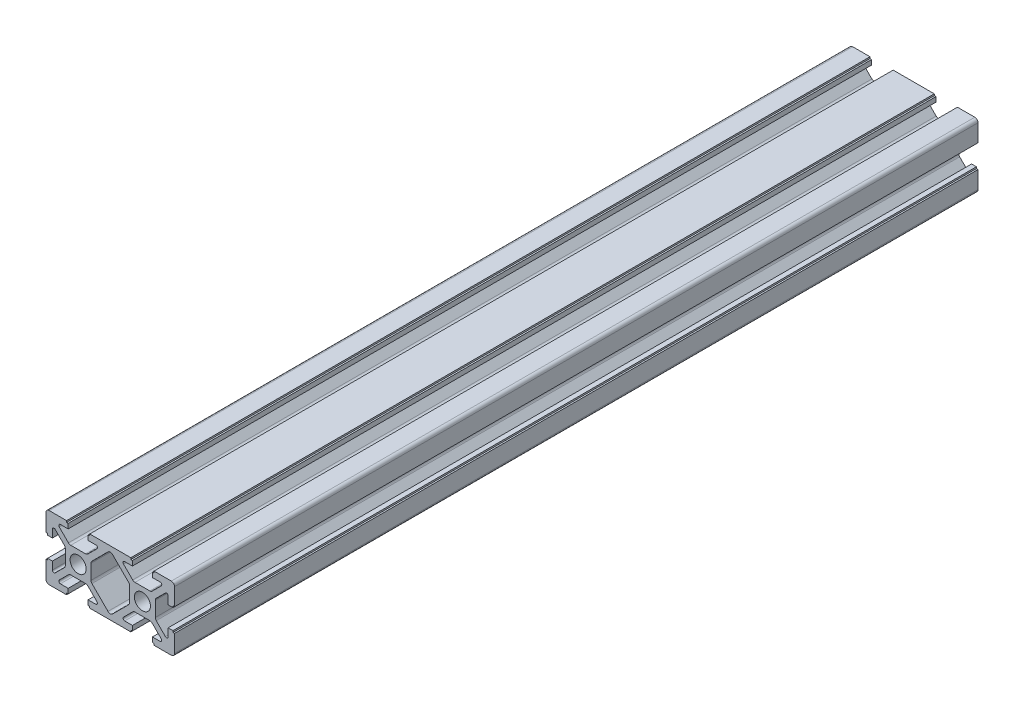
SolidWorks part; units mm, degrees
ref_plane "前视基准面" through (0, 0, 0) normal (0, 0, 1) x (1, 0, 0)
ref_plane "上视基准面" through (0, 0, 0) normal (0, 1, 0) x (1, 0, 0)
ref_plane "右视基准面" through (0, 0, 0) normal (1, 0, 0) x (0, 0, -1)
sketch "草图1" plane through (0, 0, 0) normal (0, 0, 1) x (1, 0, 0)
  line L0 (16.4868, 27.6666) -> (21.4868, 22.6666)
  line L1 (22.901, 22.6666) -> (27.901, 27.6666)
  line L2 (28.1939, 28.3737) -> (28.1939, 32.9997)
  line L3 (27.901, 33.7068) -> (22.901, 38.7068)
  line L4 (21.4868, 38.7068) -> (16.4868, 33.7068)
  line L5 (16.1939, 32.9997) -> (16.1939, 28.3737)
  line L6 (36.4868, 27.6666) -> (39.3403, 24.8131)
  line L7 (40.1939, 25.1666) -> (40.1939, 27.5867)
  line L8 (40.1939, 27.5867) -> (41.6939, 27.5867)
  line L9 (41.6939, 27.5867) -> (41.6939, 27.0867)
  line L10 (41.6939, 27.0867) -> (42.1939, 27.0867)
  line L11 (42.1939, 27.0867) -> (42.1939, 21.6867)
  line L12 (41.1939, 20.6867) -> (35.7939, 20.6867)
  line L13 (35.7939, 20.6867) -> (35.7939, 21.1867)
  line L14 (35.7939, 21.1867) -> (35.2939, 21.1867)
  line L15 (35.2939, 21.1867) -> (35.2939, 22.6867)
  line L16 (35.2939, 22.6867) -> (37.714, 22.6867)
  line L17 (38.0675, 23.5403) -> (35.214, 26.3938)
  line L18 (34.5069, 26.6867) -> (29.8809, 26.6867)
  line L19 (29.1738, 26.3938) -> (26.3202, 23.5403)
  line L20 (26.6738, 22.6867) -> (29.0939, 22.6867)
  line L21 (29.0939, 22.6867) -> (29.0939, 21.1867)
  line L22 (29.0939, 21.1867) -> (28.5939, 21.1867)
  line L23 (28.5939, 21.1867) -> (28.5939, 20.6867)
  line L24 (28.5939, 20.6867) -> (15.7939, 20.6867)
  line L25 (15.7939, 20.6867) -> (15.7939, 21.1867)
  line L26 (15.7939, 21.1867) -> (15.2939, 21.1867)
  line L27 (15.2939, 21.1867) -> (15.2939, 22.6867)
  line L28 (15.2939, 22.6867) -> (17.714, 22.6867)
  line L29 (18.0675, 23.5403) -> (15.214, 26.3938)
  line L30 (14.5069, 26.6867) -> (9.8809, 26.6867)
  line L31 (9.1738, 26.3938) -> (6.3202, 23.5403)
  line L32 (6.6738, 22.6867) -> (9.0939, 22.6867)
  line L33 (9.0939, 22.6867) -> (9.0939, 21.1867)
  line L34 (9.0939, 21.1867) -> (8.5939, 21.1867)
  line L35 (8.5939, 21.1867) -> (8.5939, 20.6867)
  line L36 (8.5939, 20.6867) -> (3.1939, 20.6867)
  line L37 (2.1939, 21.6867) -> (2.1939, 27.0867)
  line L38 (2.1939, 27.0867) -> (2.6939, 27.0867)
  line L39 (2.6939, 27.0867) -> (2.6939, 27.5867)
  line L40 (2.6939, 27.5867) -> (4.1939, 27.5867)
  line L41 (4.1939, 27.5867) -> (4.1939, 25.1666)
  line L42 (5.0474, 24.8131) -> (7.901, 27.6666)
  line L43 (8.1939, 28.3737) -> (8.1939, 32.9997)
  line L44 (7.901, 33.7068) -> (5.0474, 36.5604)
  line L45 (4.1939, 36.2068) -> (4.1939, 33.7867)
  line L46 (4.1939, 33.7867) -> (2.6939, 33.7867)
  line L47 (2.6939, 33.7867) -> (2.6939, 34.2867)
  line L48 (2.6939, 34.2867) -> (2.1939, 34.2867)
  line L49 (2.1939, 34.2867) -> (2.1939, 39.6867)
  line L50 (3.1939, 40.6867) -> (8.5939, 40.6867)
  line L51 (8.5939, 40.6867) -> (8.5939, 40.1867)
  line L52 (8.5939, 40.1867) -> (9.0939, 40.1867)
  line L53 (9.0939, 40.1867) -> (9.0939, 38.6867)
  line L54 (9.0939, 38.6867) -> (6.6738, 38.6867)
  line L55 (6.3202, 37.8332) -> (9.1738, 34.9796)
  line L56 (9.8809, 34.6867) -> (14.5069, 34.6867)
  line L57 (15.214, 34.9796) -> (18.0675, 37.8332)
  line L58 (17.714, 38.6867) -> (15.2939, 38.6867)
  line L59 (15.2939, 38.6867) -> (15.2939, 40.1867)
  line L60 (15.2939, 40.1867) -> (15.7939, 40.1867)
  line L61 (15.7939, 40.1867) -> (15.7939, 40.6867)
  line L62 (15.7939, 40.6867) -> (28.5939, 40.6867)
  line L63 (28.5939, 40.6867) -> (28.5939, 40.1867)
  line L64 (28.5939, 40.1867) -> (29.0939, 40.1867)
  line L65 (29.0939, 40.1867) -> (29.0939, 38.6867)
  line L66 (29.0939, 38.6867) -> (26.6738, 38.6867)
  line L67 (26.3202, 37.8332) -> (29.1738, 34.9796)
  line L68 (29.8809, 34.6867) -> (34.5069, 34.6867)
  line L69 (35.214, 34.9796) -> (38.0675, 37.8332)
  line L70 (37.714, 38.6867) -> (35.2939, 38.6867)
  line L71 (35.2939, 38.6867) -> (35.2939, 40.1867)
  line L72 (35.2939, 40.1867) -> (35.7939, 40.1867)
  line L73 (35.7939, 40.1867) -> (35.7939, 40.6867)
  line L74 (35.7939, 40.6867) -> (41.1939, 40.6867)
  line L75 (42.1939, 39.6867) -> (42.1939, 34.2867)
  line L76 (42.1939, 34.2867) -> (41.6939, 34.2867)
  line L77 (41.6939, 34.2867) -> (41.6939, 33.7867)
  line L78 (41.6939, 33.7867) -> (40.1939, 33.7867)
  line L79 (40.1939, 33.7867) -> (40.1939, 36.2068)
  line L80 (39.3403, 36.5604) -> (36.4868, 33.7068)
  line L81 (36.1939, 32.9997) -> (36.1939, 28.3737)
  arc A0 (17.714, 22.6867) -> (18.0675, 23.5403) centre (17.714, 23.1867) ccw
  arc A1 (15.214, 26.3938) -> (14.5069, 26.6867) centre (14.5069, 25.6867) ccw
  arc A2 (9.8809, 26.6867) -> (9.1738, 26.3938) centre (9.8809, 25.6867) ccw
  arc A3 (6.3202, 23.5403) -> (6.6738, 22.6867) centre (6.6738, 23.1867) ccw
  arc A4 (2.1939, 21.6867) -> (3.1939, 20.6867) centre (3.1939, 21.6867) ccw
  arc A5 (4.1939, 25.1666) -> (5.0474, 24.8131) centre (4.6939, 25.1666) ccw
  arc A6 (7.901, 27.6666) -> (8.1939, 28.3737) centre (7.1939, 28.3737) ccw
  arc A7 (8.1939, 32.9997) -> (7.901, 33.7068) centre (7.1939, 32.9997) ccw
  arc A8 (5.0474, 36.5604) -> (4.1939, 36.2068) centre (4.6939, 36.2068) ccw
  arc A9 (3.1939, 40.6867) -> (2.1939, 39.6867) centre (3.1939, 39.6867) ccw
  arc A10 (6.6738, 38.6867) -> (6.3202, 37.8332) centre (6.6738, 38.1867) ccw
  arc A11 (9.1738, 34.9796) -> (9.8809, 34.6867) centre (9.8809, 35.6867) ccw
  arc A12 (14.5069, 34.6867) -> (15.214, 34.9796) centre (14.5069, 35.6867) ccw
  arc A13 (18.0675, 37.8332) -> (17.714, 38.6867) centre (17.714, 38.1867) ccw
  arc A14 (26.6738, 38.6867) -> (26.3202, 37.8332) centre (26.6738, 38.1867) ccw
  arc A15 (29.1738, 34.9796) -> (29.8809, 34.6867) centre (29.8809, 35.6867) ccw
  arc A16 (34.5069, 34.6867) -> (35.214, 34.9796) centre (34.5069, 35.6867) ccw
  arc A17 (38.0675, 37.8332) -> (37.714, 38.6867) centre (37.714, 38.1867) ccw
  arc A18 (42.1939, 39.6867) -> (41.1939, 40.6867) centre (41.1939, 39.6867) ccw
  arc A19 (40.1939, 36.2068) -> (39.3403, 36.5604) centre (39.6939, 36.2068) ccw
  arc A20 (36.4868, 33.7068) -> (36.1939, 32.9997) centre (37.1939, 32.9997) ccw
  circle A21 centre (12.1939, 30.6867) radius 2.5
  circle A22 centre (32.1939, 30.6867) radius 2.5
  arc A23 (16.1939, 28.3737) -> (16.4868, 27.6666) centre (17.1939, 28.3737) ccw
  arc A24 (21.4868, 22.6666) -> (22.901, 22.6666) centre (22.1939, 23.3737) ccw
  arc A25 (27.901, 27.6666) -> (28.1939, 28.3737) centre (27.1939, 28.3737) ccw
  arc A26 (28.1939, 32.9997) -> (27.901, 33.7068) centre (27.1939, 32.9997) ccw
  arc A27 (22.901, 38.7068) -> (21.4868, 38.7068) centre (22.1939, 37.9997) ccw
  arc A28 (16.4868, 33.7068) -> (16.1939, 32.9997) centre (17.1939, 32.9997) ccw
  arc A29 (36.1939, 28.3737) -> (36.4868, 27.6666) centre (37.1939, 28.3737) ccw
  arc A30 (39.3403, 24.8131) -> (40.1939, 25.1666) centre (39.6939, 25.1666) ccw
  arc A31 (41.1939, 20.6867) -> (42.1939, 21.6867) centre (41.1939, 21.6867) ccw
  arc A32 (37.714, 22.6867) -> (38.0675, 23.5403) centre (37.714, 23.1867) ccw
  arc A33 (35.214, 26.3938) -> (34.5069, 26.6867) centre (34.5069, 25.6867) ccw
  arc A34 (29.8809, 26.6867) -> (29.1738, 26.3938) centre (29.8809, 25.6867) ccw
  arc A35 (26.3202, 23.5403) -> (26.6738, 22.6867) centre (26.6738, 23.1867) ccw
extrude "拉伸1" add sketch "草图1" along normal blind 250
ref_plane "基准面1" through (0, 0, 125) normal (0, 0, 1) x (1, 0, 0)
ref_plane "基准面2" through (22.1939, 0, 0) normal (1, 0, 0) x (0, 0, -1)
ref_plane "基准面3" through (0, 30.6867, 0) normal (0, 1, 0) x (1, 0, 0)
